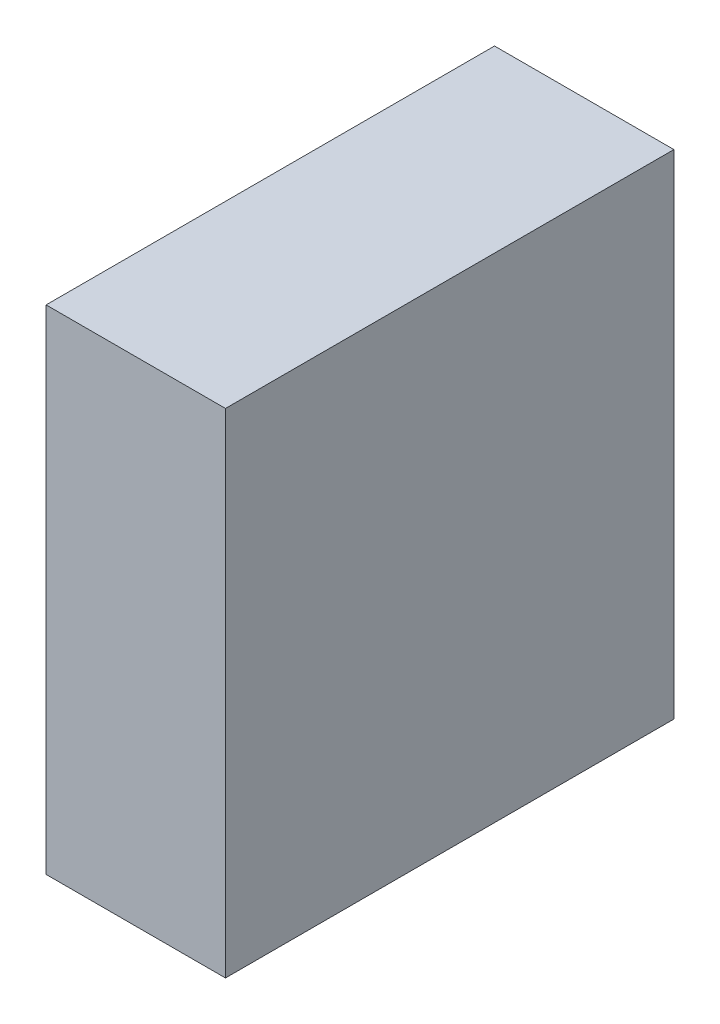
SolidWorks part; units mm, degrees
ref_plane "前视基准面" through (0, 0, 0) normal (0, 0, 1) x (1, 0, 0)
ref_plane "上视基准面" through (0, 0, 0) normal (0, 1, 0) x (1, 0, 0)
ref_plane "右视基准面" through (0, 0, 0) normal (1, 0, 0) x (0, 0, -1)
other "Configuration Table"
sketch "草图1" plane through (0, 0, 0) normal (0, 0, 1) x (1, 0, 0)
  line L0 (0, 0) -> (2, 0)
  line L1 (2, 0) -> (2, 5.5)
  line L2 (2, 5.5) -> (0, 5.5)
  line L3 (0, 5.5) -> (0, 0)
  dimension "width" = 2
  dimension "height" = 5.5
extrude "Compact_yoke" add sketch "草图1" along normal blind 5
